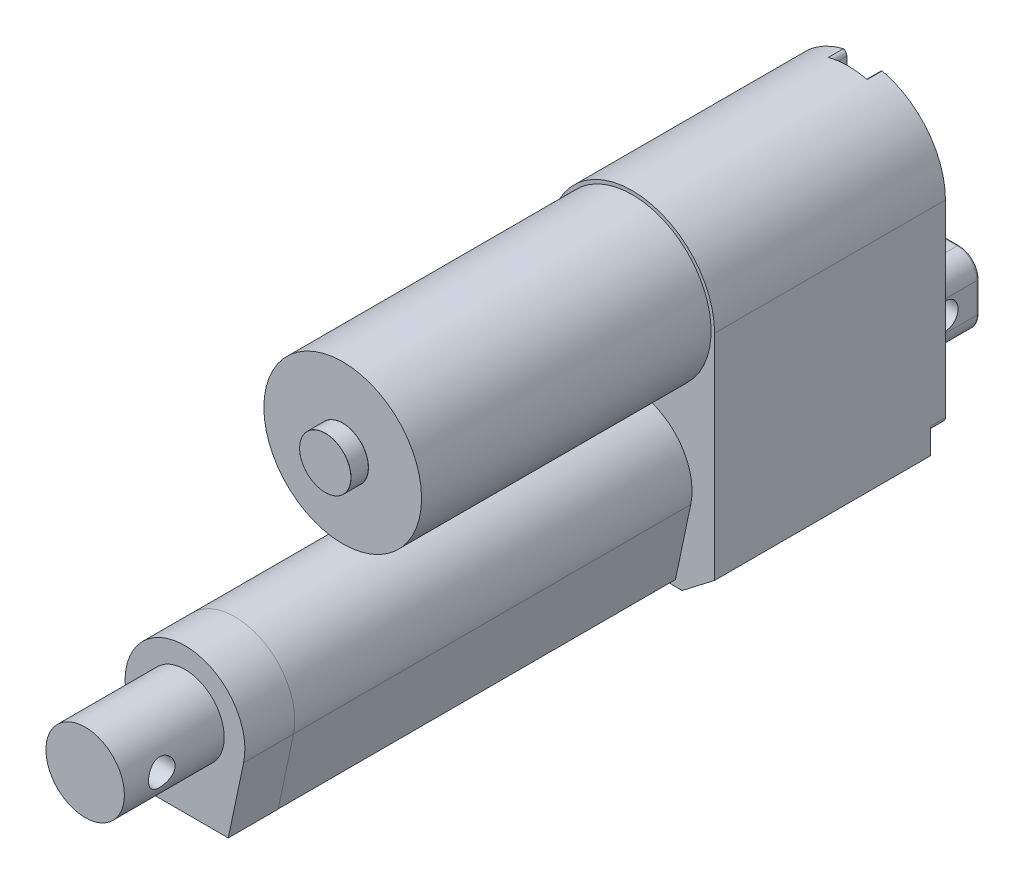
SolidWorks part; units mm, degrees
ref_plane "Front Plane" through (0, 0, 0) normal (0, 0, 1) x (1, 0, 0)
ref_plane "Top Plane" through (0, 0, 0) normal (0, 1, 0) x (1, 0, 0)
ref_plane "Right Plane" through (0, 0, 0) normal (1, 0, 0) x (0, 0, -1)
sketch "Sketch1" plane through (0, 0, 0) normal (0, 0, 1) x (1, 0, 0)
  line L0 (-12.7, 0) -> (12.7, 0)
  line L1 (-20.955, 6.35) -> (-20.955, 60.833)
  line L2 (20.955, 6.35) -> (20.955, 60.833)
  line L3 (12.7, 0) -> (20.955, 6.35)
  line L4 (-20.955, 6.35) -> (-12.7, 0)
  arc A0 (-20.955, 60.833) -> (20.955, 60.833) centre (0, 60.833) cw
  point P0 (0, 81.788)
  dimension "D7" = 81.788
  dimension "D1" = 41.91
  dimension "D2" = 8.255
  dimension "D3" = 12.7
  dimension "D4" = 8.255
  dimension "D5" = 12.7
  dimension "D6" = 6.35
extrude "Boss-Extrude1" add sketch "Sketch1" along normal blind 58.7375
sketch "Sketch2" plane through (0, 0, 58.7375) normal (0, 0, 1) x (1, 0, 0)
  circle A0 centre (0, 60.833) radius 20.066
  arc A1 (20.955, 60.833) -> (-20.955, 60.833) centre (0, 60.833) ccw construction
  dimension "D1" = 40.132
extrude "Boss-Extrude2" add sketch "Sketch2" along normal blind 73.66
sketch "Sketch3" plane through (0, 0, 58.7375) normal (0, 0, 1) x (1, 0, 0)
  line L0 (-12.7, 0) -> (12.7, 0) construction
  line L1 (-14.8881, 20.0427) -> (-10.9969, 1.5621)
  line L2 (-10.9969, 1.5621) -> (10.9969, 1.5621)
  line L3 (10.9969, 1.5621) -> (14.8881, 20.0427)
  line L5 (-10.9969, 1.5621) -> (-10.668, 0) construction
  line L6 (10.9969, 1.5621) -> (10.668, 0) construction
  arc A0 (14.8881, 20.0427) -> (-14.8881, 20.0427) centre (0, 23.1775) ccw
  point P1 (0, 1.5621)
  point P6 (15.2146, 23.1775)
  point P11 (-15.2146, 23.1775)
  point P16 (0, 38.3921)
  dimension "D1" = 23.1775
  dimension "D3" = 36.83
  dimension "D2" = 30.4292
  dimension "D4" = 21.336
extrude "EDIT_LENGTH_HERE (hover for comment)" add sketch "Sketch3" along normal blind 113.792
sketch "Sketch4" plane through (0, 0, 172.5295) normal (0, 0, 1) x (1, 0, 0)
  circle A0 centre (0, 23.1775) radius 9.9822
  arc A1 (14.8881, 20.0427) -> (-14.8881, 20.0427) centre (0, 23.1775) ccw construction
  dimension "D3" = 19.9644
extrude "Boss-Extrude4" add sketch "Sketch4" along normal blind 25.4
sketch "Sketch5" plane through (0, 0, 0) normal (0, 0, -1) x (-1, 0, 0)
  line L0 (12.7, 0) -> (-12.7, 0) construction
  line L1 (-3.81, 32.0675) -> (3.81, 32.0675)
  line L2 (-8.89, 26.9875) -> (-8.89, 19.3675)
  line L3 (-3.81, 14.2875) -> (3.81, 14.2875)
  line L4 (8.89, 26.9875) -> (8.89, 19.3675)
  line L5 (-8.89, 32.0675) -> (8.89, 14.2875) construction
  line L6 (-8.89, 14.2875) -> (8.89, 32.0675) construction
  arc A0 (-8.89, 19.3675) -> (-3.81, 14.2875) centre (-3.81, 19.3675) ccw
  arc A1 (3.81, 14.2875) -> (8.89, 19.3675) centre (3.81, 19.3675) ccw
  arc A2 (3.81, 32.0675) -> (8.89, 26.9875) centre (3.81, 26.9875) cw
  arc A3 (-3.81, 32.0675) -> (-8.89, 26.9875) centre (-3.81, 26.9875) ccw
  point P0 (0, 23.1775)
  dimension "D4" = 5.08
  dimension "D1" = 17.78
  dimension "D2" = 17.78
  dimension "D3" = 14.2875
extrude "Boss-Extrude5" add sketch "Sketch5" along normal blind 20.6502
sketch "Sketch6" plane through (8.89, 0, 0) normal (1, 0, 0) x (0, 0, -1)
  line L0 (11.9062, 14.2875) -> (11.9062, 32.0675) construction
  line L1 (0, 26.9875) -> (0, 19.3675) construction
  line L2 (20.6502, 14.2875) -> (0, 14.2875) construction
  line L3 (-197.9295, 33.1597) -> (-197.9295, 13.1953) construction
  line L4 (20.6502, 32.0675) -> (0, 32.0675) construction
  circle A0 centre (11.9062, 23.1775) radius 3.3782
  circle A1 centre (-188.4045, 23.1775) radius 3.3782
  dimension "D1" = 6.7564
  dimension "D3" = 6.7564
  dimension "D2" = 11.9062
  dimension "D4" = 9.525
extrude "Cut-Extrude3" cut sketch "Sketch6" against normal through all and the other way through all
fillet "Fillet1" radius 2.54 8 edges at (-7.4021, 15.7754, 0) (0, 14.2875, 0) (7.4021, 15.7754, 0) (8.89, 23.1775, 0) (7.4021, 30.5796, 0) (0, 32.0675, 0) (-7.4021, 30.5796, 0) (-8.89, 23.1775, 0)
fillet "Fillet2" radius 0.508 8 edges at (8.89, 23.1775, -20.6502) (7.4021, 30.5796, -20.6502) (0, 32.0675, -20.6502) (-7.4021, 30.5796, -20.6502) (-8.89, 23.1775, -20.6502) (-7.4021, 15.7754, -20.6502) (0, 14.2875, -20.6502) (7.4021, 15.7754, -20.6502)
sketch "Sketch7" plane through (0, 0, 0) normal (0, 0, -1) x (-1, 0, 0)
  line L0 (-4.1275, 77.089) -> (-4.1275, 80.0683)
  line L1 (4.1275, 77.089) -> (4.1275, 79.9786)
  line L2 (-20.955, 6.35) -> (-20.955, 60.833) construction
  line L3 (20.955, 60.833) -> (20.955, 6.35) construction
  line L4 (-13.3956, 1.8544) -> (-11.2223, 6.0477)
  line L5 (-14.605, 11.6109) -> (-19.685, 11.6109)
  line L6 (11.5416, 5.5356) -> (13.4023, 1.8413)
  line L7 (14.605, 11.6109) -> (19.685, 11.6109)
  line L8 (20.955, 6.35) -> (12.7, 0) construction
  line L9 (-12.7, 0) -> (-20.955, 6.35) construction
  line L10 (-20.955, 6.35) -> (-20.955, 12.8809)
  line L11 (12.7, 0) -> (-12.7, 0) construction
  line L12 (-12.7, 0) -> (-20.955, 6.35)
  line L13 (20.955, 12.8809) -> (20.955, 6.35)
  line L14 (20.955, 6.35) -> (12.7, 0)
  arc A0 (-4.1275, 77.089) -> (4.1275, 77.089) centre (0, 77.089) ccw
  arc A1 (20.955, 60.833) -> (-20.955, 60.833) centre (0, 60.833) ccw construction
  arc A2 (6.3689, 80.7967) -> (-6.4572, 80.7683) centre (0, 60.833) ccw
  arc A3 (-6.4572, 80.7683) -> (-4.1275, 80.0683) centre (-5.3975, 80.0683) cw
  arc A4 (4.1275, 79.9786) -> (6.3689, 80.7967) centre (5.3975, 79.9786) cw
  arc A5 (-11.2223, 6.0477) -> (-14.605, 11.6109) centre (-14.605, 7.8009) ccw
  arc A6 (14.605, 11.6109) -> (11.5416, 5.5356) centre (14.605, 7.8009) ccw
  arc A7 (13.4023, 1.8413) -> (12.268, 0) centre (12.268, 1.27) cw
  arc A8 (-13.3956, 1.8544) -> (-12.268, 0) centre (-12.268, 1.27) ccw
  arc A9 (19.685, 11.6109) -> (20.955, 12.8809) centre (19.685, 12.8809) ccw
  arc A10 (-19.685, 11.6109) -> (-20.955, 12.8809) centre (-19.685, 12.8809) cw
  point P12 (4.6513, 81.2653)
  point P39 (20.955, 11.6109)
  point P42 (-20.955, 11.6109)
  line M10 (20.955, 6.35) -> (20.955, 60.833)
  arc M11 (20.955, 60.833) -> (-20.955, 60.833) centre (0, 60.833) ccw
  line M12 (-20.955, 60.833) -> (-20.955, 6.35)
  line M13 (-20.955, 6.35) -> (-12.7, 0)
  dimension "D1" = 8.255
  dimension "D2" = 1.27
  dimension "D3" = 1.27
  dimension "D5" = 7.62
  dimension "D8" = 1.27
  dimension "D9" = 1.27
  dimension "D4" = 16.256
  dimension "D6" = 6.35
  dimension "D7" = 6.35
extrude "Cut-Extrude5" cut sketch "Sketch7" against normal blind 3.81 contours L1 A4 A3 L0 A0 M11 | L5 A10 A8 L4 A5 M12 M13 | A9 L7 A6 L6 A7 L14 M10
sketch "Sketch8" plane through (0, 0, 132.3975) normal (0, 0, 1) x (1, 0, 0)
  circle A0 centre (0, 60.833) radius 6.5405
  dimension "D1" = 13.081
extrude "Boss-Extrude6" add sketch "Sketch8" along normal blind 4.445
fillet "Fillet3" radius 0.0254 2 edges at (6.5405, 60.833, 132.3975) (6.5405, 60.833, 136.8425)
sketch "Sketch9" plane through (0, 0, 172.5295) normal (0, 0, 1) x (1, 0, 0)
  line L0 (10.9969, 1.5621) -> (14.8881, 20.0427) construction
  line L1 (-14.8881, 20.0427) -> (-10.9969, 1.5621) construction
  line L2 (-10.9969, 1.5621) -> (10.9969, 1.5621) construction
  line L3 (10.9969, 1.5621) -> (14.8881, 20.0427)
  line L4 (-14.8881, 20.0427) -> (-10.9969, 1.5621)
  line L5 (-10.9969, 1.5621) -> (10.9969, 1.5621)
  line L6 (-11.0175, 1.5367) -> (11.0175, 1.5367)
  line L7 (11.0175, 1.5367) -> (14.913, 20.0374)
  line L8 (-14.913, 20.0374) -> (-11.0175, 1.5367)
  arc A0 (14.8881, 20.0427) -> (-14.8881, 20.0427) centre (0, 23.1775) ccw construction
  arc A1 (14.8881, 20.0427) -> (-14.8881, 20.0427) centre (0, 23.1775) ccw
  arc A2 (14.913, 20.0374) -> (-14.913, 20.0374) centre (0, 23.1775) ccw
  dimension "D1" = 0.0254
extrude "Boss-Extrude7" add sketch "Sketch9" against normal blind 12.7
sketch "Sketch10" plane through (0, 0, 3.81) normal (0, 0, -1) x (-1, 0, 0)
  circle A0 centre (0, 77.089) radius 2.54
  circle A1 centre (-14.605, 7.8009) radius 2.54
  circle A2 centre (14.605, 7.8009) radius 2.54
  dimension "D1" = 5.08
extrude "Boss-Extrude8" add sketch "Sketch10" along normal blind 0.635
sketch "Sketch12" plane through (0, 0, 3.175) normal (0, 0, -1) x (-1, 0, 0)
  line L0 (0.3175, 74.3343) -> (0.3175, 75.8444)
  line L1 (-0.2921, 78.359) -> (0.2921, 78.359)
  line L2 (-0.3175, 78.3336) -> (-0.3175, 77.5335)
  line L3 (-0.2921, 75.819) -> (0.2921, 75.819)
  line L4 (0.3175, 78.3336) -> (0.3175, 77.5335)
  line L5 (-0.3175, 78.359) -> (0.3175, 75.819) construction
  line L6 (-0.3175, 75.819) -> (0.3175, 78.359) construction
  line L7 (-1.2446, 77.4065) -> (-0.4445, 77.4065)
  line L8 (-1.27, 77.3811) -> (-1.27, 76.7969)
  line L9 (-1.2446, 76.7715) -> (-0.4445, 76.7715)
  line L10 (1.27, 77.3811) -> (1.27, 76.7763)
  line L11 (-1.27, 77.4065) -> (1.27, 76.7715) construction
  line L12 (-1.27, 76.7715) -> (1.27, 77.4065) construction
  line L13 (0.3264, 74.381) -> (1.2682, 76.767)
  line L14 (-14.2875, 7.3564) -> (-14.2875, 6.5563)
  line L15 (0.4445, 77.4065) -> (1.2446, 77.4065)
  line L16 (-0.3175, 76.6445) -> (-0.3175, 75.8444)
  line L17 (-14.8971, 9.0709) -> (-14.3129, 9.0709)
  line L18 (-14.9225, 9.0455) -> (-14.9225, 8.2454)
  line L19 (-14.8971, 6.5309) -> (-14.3129, 6.5309)
  line L20 (-14.2875, 9.0455) -> (-14.2875, 8.2454)
  line L21 (-14.9225, 9.0709) -> (-14.2875, 6.5309) construction
  line L22 (-14.9225, 6.5309) -> (-14.2875, 9.0709) construction
  line L23 (-15.8496, 8.1184) -> (-15.0495, 8.1184)
  line L24 (-15.875, 8.093) -> (-15.875, 7.5088)
  line L25 (-15.8496, 7.4834) -> (-15.0495, 7.4834)
  line L26 (-13.335, 8.093) -> (-13.335, 7.5088)
  line L27 (-15.875, 8.1184) -> (-13.335, 7.4834) construction
  line L28 (-15.875, 7.4834) -> (-13.335, 8.1184) construction
  line L29 (-14.1605, 7.4834) -> (-13.3604, 7.4834)
  line L30 (-14.1605, 8.1184) -> (-13.3604, 8.1184)
  line L31 (-14.9225, 7.3564) -> (-14.9225, 6.5563)
  line L32 (14.9225, 7.3564) -> (14.9225, 6.5563)
  line L33 (14.3129, 9.0709) -> (14.8971, 9.0709)
  line L34 (14.2875, 9.0455) -> (14.2875, 8.2454)
  line L35 (14.3129, 6.5309) -> (14.8971, 6.5309)
  line L36 (14.9225, 9.0455) -> (14.9225, 8.2454)
  line L37 (14.2875, 9.0709) -> (14.9225, 6.5309) construction
  line L38 (14.2875, 6.5309) -> (14.9225, 9.0709) construction
  line L39 (13.3604, 8.1184) -> (14.1605, 8.1184)
  line L40 (13.335, 8.093) -> (13.335, 7.5088)
  line L41 (13.3604, 7.4834) -> (14.1605, 7.4834)
  line L42 (15.875, 8.093) -> (15.875, 7.5088)
  line L43 (13.335, 8.1184) -> (15.875, 7.4834) construction
  line L44 (13.335, 7.4834) -> (15.875, 8.1184) construction
  line L45 (15.0495, 7.4834) -> (15.8496, 7.4834)
  line L46 (15.0495, 8.1184) -> (15.8496, 8.1184)
  line L47 (14.2875, 7.3564) -> (14.2875, 6.5055)
  arc A0 (-0.4445, 76.7715) -> (-0.3175, 76.6445) centre (-0.4445, 76.6445) cw
  arc A1 (0.3264, 74.381) -> (0.3175, 74.3343) centre (0.4445, 74.3343) ccw
  arc A2 (0.3175, 77.5335) -> (0.4445, 77.4065) centre (0.4445, 77.5335) ccw
  arc A3 (-0.4445, 77.4065) -> (-0.3175, 77.5335) centre (-0.4445, 77.5335) ccw
  arc A4 (-1.2446, 77.4065) -> (-1.27, 77.3811) centre (-1.2446, 77.3811) ccw
  arc A5 (-1.27, 76.7969) -> (-1.2446, 76.7715) centre (-1.2446, 76.7969) ccw
  arc A6 (-0.3175, 75.8444) -> (-0.2921, 75.819) centre (-0.2921, 75.8444) ccw
  arc A7 (0.2921, 75.819) -> (0.3175, 75.8444) centre (0.2921, 75.8444) ccw
  arc A8 (1.2682, 76.767) -> (1.27, 76.7763) centre (1.2446, 76.7763) ccw
  arc A9 (1.2446, 77.4065) -> (1.27, 77.3811) centre (1.2446, 77.3811) cw
  arc A10 (0.2921, 78.359) -> (0.3175, 78.3336) centre (0.2921, 78.3336) cw
  arc A11 (-0.2921, 78.359) -> (-0.3175, 78.3336) centre (-0.2921, 78.3336) ccw
  arc A12 (-15.0495, 7.4834) -> (-14.9225, 7.3564) centre (-15.0495, 7.3564) cw
  arc A13 (-14.1605, 7.4834) -> (-14.2875, 7.3564) centre (-14.1605, 7.3564) ccw
  arc A14 (-14.2875, 8.2454) -> (-14.1605, 8.1184) centre (-14.1605, 8.2454) ccw
  arc A15 (-15.0495, 8.1184) -> (-14.9225, 8.2454) centre (-15.0495, 8.2454) ccw
  arc A16 (-15.8496, 8.1184) -> (-15.875, 8.093) centre (-15.8496, 8.093) ccw
  arc A17 (-15.875, 7.5088) -> (-15.8496, 7.4834) centre (-15.8496, 7.5088) ccw
  arc A18 (-14.9225, 6.5563) -> (-14.8971, 6.5309) centre (-14.8971, 6.5563) ccw
  arc A19 (-14.3129, 6.5309) -> (-14.2875, 6.5563) centre (-14.3129, 6.5563) ccw
  arc A20 (-13.3604, 7.4834) -> (-13.335, 7.5088) centre (-13.3604, 7.5088) ccw
  arc A21 (-13.3604, 8.1184) -> (-13.335, 8.093) centre (-13.3604, 8.093) cw
  arc A22 (-14.3129, 9.0709) -> (-14.2875, 9.0455) centre (-14.3129, 9.0455) cw
  arc A23 (-14.8971, 9.0709) -> (-14.9225, 9.0455) centre (-14.8971, 9.0455) ccw
  arc A26 (14.1605, 7.4834) -> (14.2875, 7.3564) centre (14.1605, 7.3564) cw
  arc A27 (15.0495, 7.4834) -> (14.9225, 7.3564) centre (15.0495, 7.3564) ccw
  arc A28 (14.9225, 8.2454) -> (15.0495, 8.1184) centre (15.0495, 8.2454) ccw
  arc A29 (14.1605, 8.1184) -> (14.2875, 8.2454) centre (14.1605, 8.2454) ccw
  arc A30 (13.3604, 8.1184) -> (13.335, 8.093) centre (13.3604, 8.093) ccw
  arc A31 (13.335, 7.5088) -> (13.3604, 7.4834) centre (13.3604, 7.5088) ccw
  arc A32 (14.2875, 6.5055) -> (14.3129, 6.5309) centre (14.3129, 6.5055) ccw
  arc A33 (14.8971, 6.5309) -> (14.9225, 6.5563) centre (14.8971, 6.5563) ccw
  arc A34 (15.8496, 7.4834) -> (15.875, 7.5088) centre (15.8496, 7.5088) ccw
  arc A35 (15.8496, 8.1184) -> (15.875, 8.093) centre (15.8496, 8.093) cw
  arc A36 (14.8971, 9.0709) -> (14.9225, 9.0455) centre (14.8971, 9.0455) cw
  arc A37 (14.3129, 9.0709) -> (14.2875, 9.0455) centre (14.3129, 9.0455) ccw
  point P0 (0, 77.089)
  point P6 (0, 77.089)
  point P16 (-0.3175, 76.7715)
  point P20 (0.3175, 74.3585)
  point P23 (0.3175, 77.4065)
  point P50 (-14.605, 7.8009)
  point P55 (-14.605, 7.8009)
  point P96 (14.605, 7.8009)
  point P101 (14.605, 7.8009)
  dimension "D5" = 0.127
  dimension "D6" = 0.0254
  dimension "D11" = 0.127
  dimension "D12" = 0.0254
  dimension "D17" = 0.127
  dimension "D18" = 0.0254
  dimension "D1" = 0.635
  dimension "D2" = 2.54
  dimension "D3" = 0.635
  dimension "D4" = 2.54
  dimension "D7" = 0.635
  dimension "D8" = 2.54
  dimension "D9" = 0.635
  dimension "D10" = 2.54
  dimension "D13" = 0.635
  dimension "D14" = 2.54
  dimension "D15" = 0.635
  dimension "D16" = 2.54
dome "Dome1" [suppressed] faces to dome 3 distance 1.27 parameters "D1"=1.27
extrude "Cut-Extrude7" [suppressed] cut sketch "Sketch12" along normal up to next
